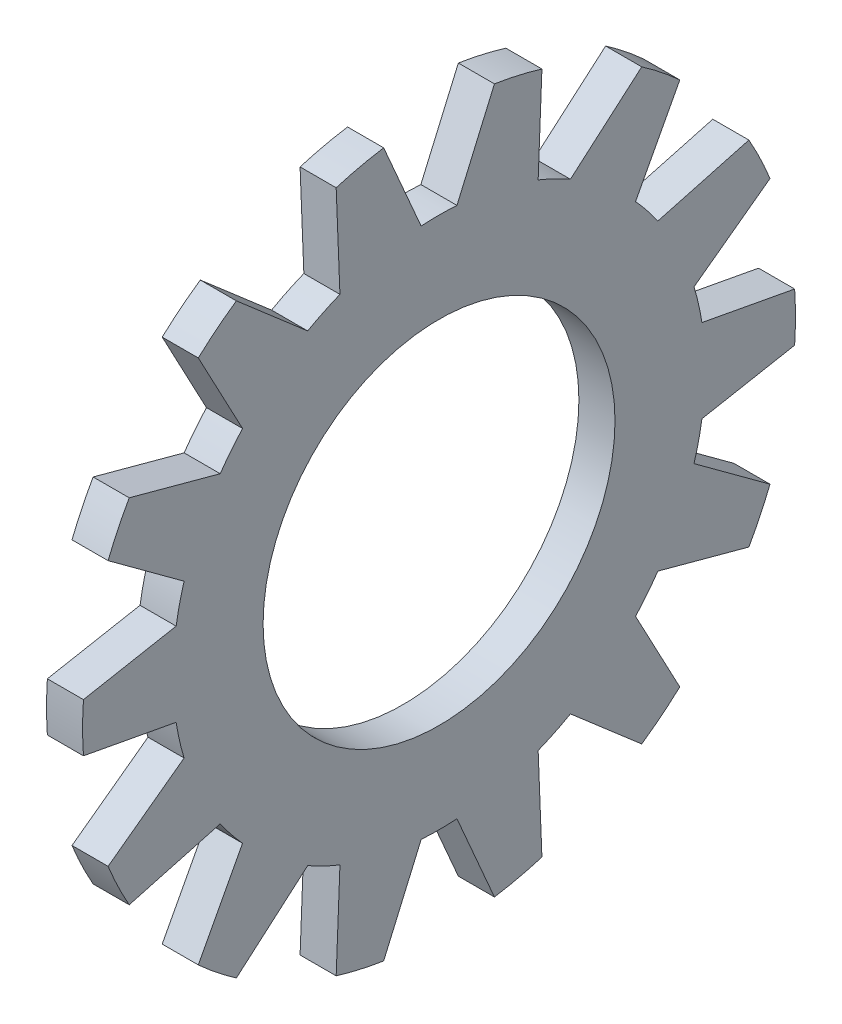
SolidWorks part; units mm, degrees
ref_plane "Plane1" through (0, 0, 0) normal (0, 0, 1) x (1, 0, 0)
ref_plane "Plane2" through (0, 0, 0) normal (0, 1, 0) x (1, 0, 0)
ref_plane "Plane3" through (0, 0, 0) normal (1, 0, 0) x (0, 0, -1)
sketch "SecSke" plane through (0, 0, 0) normal (0, 0, 1) x (1, 0, 0)
  line L0 (-34.925, 0) -> (9.525, 0) construction
  line L1 (0, 2.4765) -> (0, 5.0165)
  line L2 (0, 5.0165) -> (-0.508, 5.0165)
  line L3 (-0.508, 5.0165) -> (-0.508, 2.4765)
  line L4 (-0.508, 2.4765) -> (0, 2.4765)
  dimension "Thickness" = 0.508
  dimension "Inside_dia" = 4.953
  dimension "Outside_dia" = 10.033
revolve "Body" add sketch "SecSke" angle 360 about L0
sketch "ExtCutSke" plane through (0, 0, 0) normal (1, 0, 0) x (0, 0, -1)
  line L0 (0, 0) -> (0, 5.2673) construction
  line L1 (-0.8823, 5.1929) -> (-0.252, 3.738)
  line L2 (0.8823, 5.1929) -> (0.252, 3.738)
  arc A0 (0.8823, 5.1929) -> (-0.8823, 5.1929) centre (0, 0) ccw
  arc A1 (0.252, 3.738) -> (-0.252, 3.738) centre (0, 0) ccw
  dimension "Cut_dia" = 7.493
  dimension "Clr_dia" = 10.5347
  dimension "Cut_ang" = 7.714
  dimension "Clr_ang" = 19.286
extrude "ExtCut" cut sketch "ExtCutSke" against normal through all
pattern_circular "ExtCuts" count 14 over 360 about axis through (0, 0, 0) along (1, 0, 0) of "ExtCut"
equation "' \"Inside_dia@SecSke\" = 16"
equation "' \"Outside_dia@SecSke\" = 26"
equation "' \"Thickness@SecSke\" = 1.2"
equation "' \"Count@ExtCuts\" = 14"
equation "' \"Inside_dia@SecSke\" = 10.5"
equation "' \"Outside_dia@SecSke\" = 18"
equation "' \"Thickness@SecSke\" = 0.9"
equation "' \"Count@ExtCuts\" = 12"
equation "' \"Inside_dia@SecSke\" = 6.4"
equation "' \"Outside_dia@SecSke\" = 11"
equation "' \"Thickness@SecSke\" = 0.6"
equation "' \"Inside_dia@SecSke\" = 4.3"
equation "' \"Outside_dia@SecSke\" = 8.5"
equation "' \"Thickness@SecSke\" = 0.45"
equation "' \"Count@ExtCuts\" = 9"
equation "\"Angle@ExtCuts\" = 360 / \"Count@ExtCuts\""
equation "\"Clr_dia@ExtCutSke\" =  \"Outside_dia@SecSke\" * 1.05"
equation "\"Cut_dia@ExtCutSke\" = \"Outside_dia@SecSke\" - (\"Outside_dia@SecSke\"  - \"Inside_dia@SecSke\" ) * 0.5"
equation "\"Clr_ang@ExtCutSke\" = (360 / \"Count@ExtCuts\") * 0.75"
equation "\"Cut_ang@ExtCutSke\" = (360 / \"Count@ExtCuts\") * 0.3"
